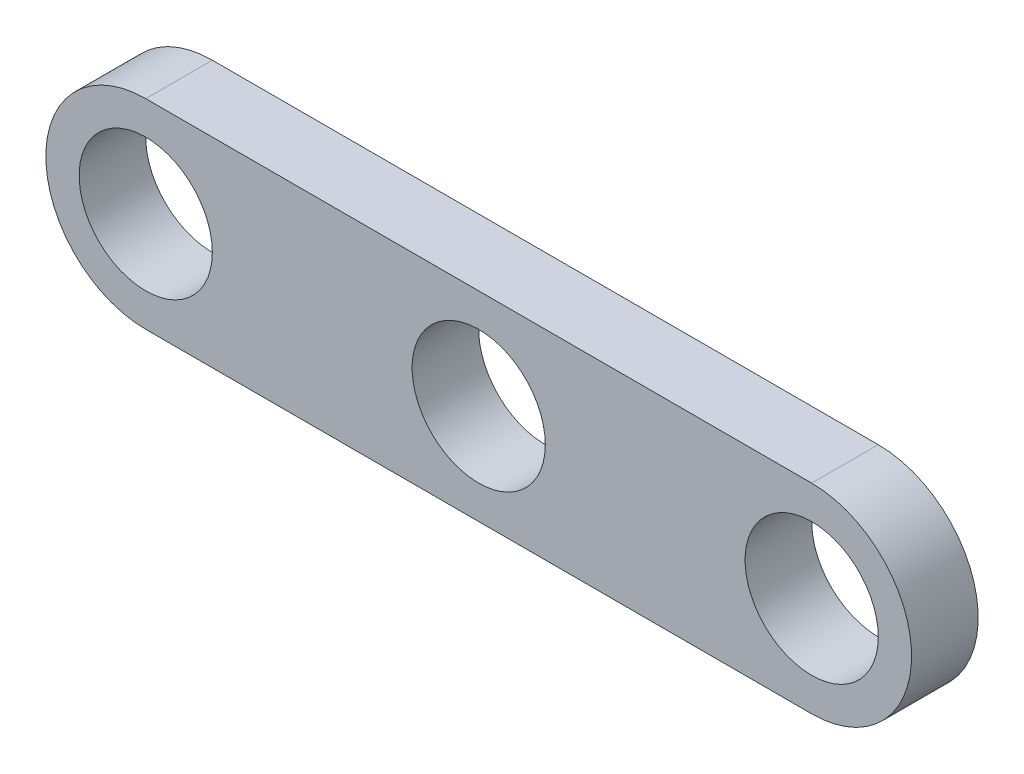
SolidWorks part; units mm, degrees
ref_plane "Front Plane" through (0, 0, 0) normal (0, 0, 1) x (1, 0, 0)
ref_plane "Top Plane" through (0, 0, 0) normal (0, 1, 0) x (1, 0, 0)
ref_plane "Right Plane" through (0, 0, 0) normal (1, 0, 0) x (0, 0, -1)
sketch "Sketch2" plane through (0, 0, 0) normal (0, 0, 1) x (1, 0, 0)
  line L1 (0, 0) -> (-20, 0)
  line L2 (0, 0) -> (0, 6)
  line L3 (0, 6) -> (-20, 6)
  line L4 (-20, 0) -> (-20, 6)
  arc A0 (-20, 6) -> (-20, 0) centre (-20, 3) ccw
  arc A1 (0, 0) -> (0, 6) centre (0, 3) ccw
extrude "Boss-Extrude2" add sketch "Sketch2" along normal blind 2 contours L4 A0 | L4 L1 L2 L3 | L2 A1
sketch "Sketch4" plane through (0, 0, 2) normal (0, 0, 1) x (1, 0, 0)
  line L0 (-20, 6) -> (-20, 0)
  line L1 (0, 6) -> (0, 0)
  line L2 (-10, 6) -> (-10, 0)
  line L3 (0, 6) -> (-20, 6) construction
  line L4 (0, 0) -> (-20, 0) construction
  circle A0 centre (-20, 3) radius 2
  circle A1 centre (-10, 3) radius 2
  circle A2 centre (0, 3) radius 2
extrude "Cut-Extrude1" cut sketch "Sketch4" against normal blind 6 contours L0 A0 | L0 A0 | L2 A1 | L2 A1 | L1 A2 | L1 A2
